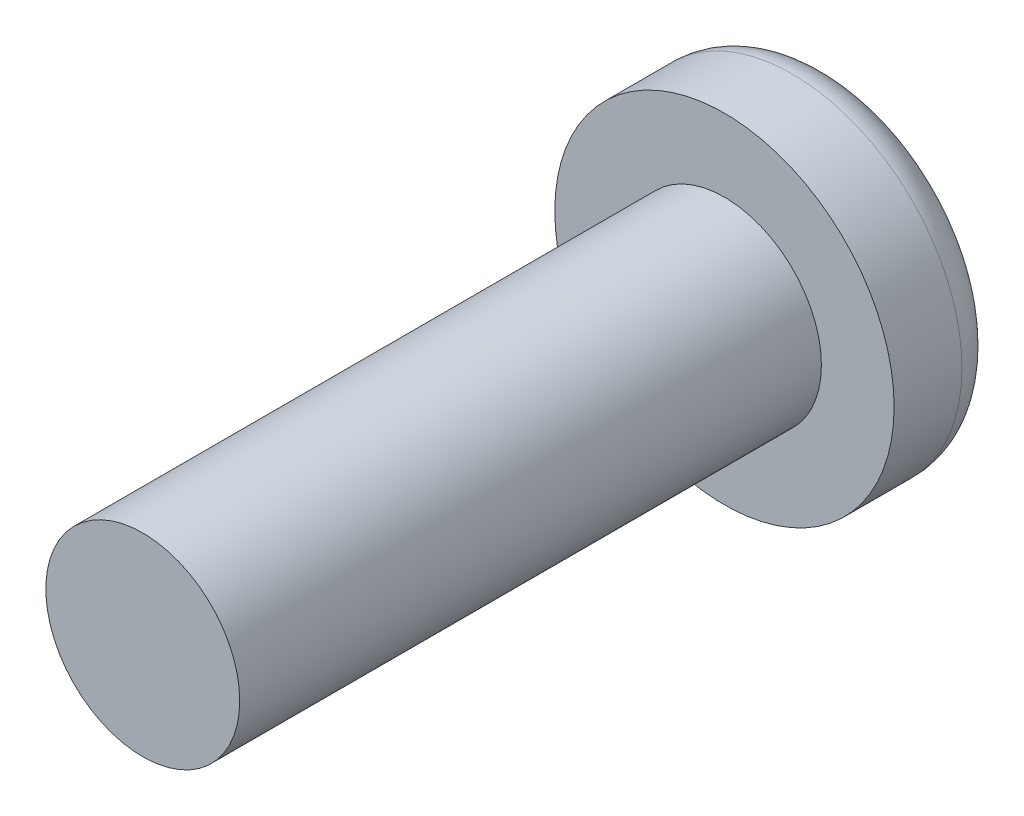
SolidWorks part; units mm, degrees
ref_plane "前视基准面" through (0, 0, 0) normal (0, 0, 1) x (1, 0, 0)
ref_plane "上视基准面" through (0, 0, 0) normal (0, 1, 0) x (1, 0, 0)
ref_plane "右视基准面" through (0, 0, 0) normal (1, 0, 0) x (0, 0, -1)
sketch "草图1" plane through (0, 0, 0) normal (0, 0, 1) x (1, 0, 0)
  circle A0 centre (0, 0) radius 5
extrude "凸台-拉伸1" add sketch "草图1" along normal blind 30 contours A0
sketch "草图2" plane through (0, 0, 0) normal (0, 0, -1) x (-1, 0, 0)
  circle A0 centre (0, 0) radius 8.75
  dimension "D1" = 17.5
extrude "凸台-拉伸2" add sketch "草图2" along normal blind 5.5
fillet "圆角2" radius 2 1 edges at (-8.75, 0, -5.5)
thread "螺纹线1" pitch 0.9071 start angle 0, offset 0, length 30, pitch 0.9071, diameter 10
ref_plane "基准面2" through (5, 0, 0) normal (0, -1, 0) x (1, 0, 0)
sketch "螺纹线轮廓2" plane through (5, 0, 0) normal (0, -1, 0) x (1, 0, 0)
  line L0 (0, 0) -> (0, 0.9071) construction
  line L11 (0, 0) -> (0, 0.7937)
  line L12 (0, 0.7937) -> (-0.491, 0.5103)
  line L13 (-0.491, 0.5103) -> (-0.491, 0.2835)
  line L15 (-0.491, 0.2835) -> (0, 0)
  line L17 (-0.491, 0.3969) -> (0, 0.3969) construction
  point P2 (0, 0)
  dimension "Pitch" = 0.9071
  dimension "Profile_Angle" = 60
  dimension "Profile_Land" = 0.2268
  dimension "Profile_Height" = 0.491
